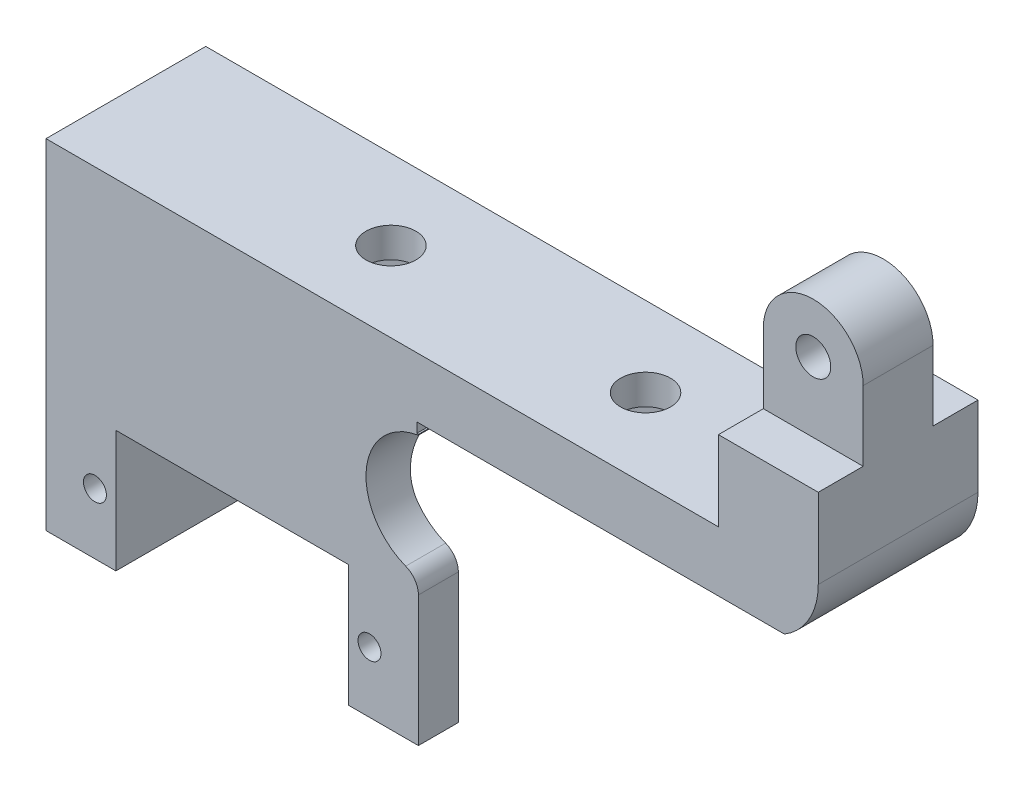
SolidWorks part; units mm, degrees
ref_plane "Plan de face" through (0, 0, 0) normal (0, 0, 1) x (1, 0, 0)
ref_plane "Plan de dessus" through (0, 0, 0) normal (0, 1, 0) x (1, 0, 0)
ref_plane "Plan de droite" through (0, 0, 0) normal (1, 0, 0) x (0, 0, -1)
sketch "Esquisse1" plane through (0, 0, 0) normal (0, 0, 1) x (1, 0, 0)
  line L0 (0, 0) -> (67.35, 0)
  line L1 (67.35, 0) -> (67.35, 20)
  line L2 (67.35, 20) -> (77.35, 20)
  line L3 (0, 0) -> (0, -34)
  line L4 (0, -34) -> (7, -34)
  line L5 (7, -34) -> (7, -7)
  line L6 (7, -7) -> (30.3, -7)
  line L7 (30.3, -7) -> (30.3, -34)
  line L8 (30.3, -34) -> (37.3, -34)
  line L9 (37.3, -34) -> (37.3, -7)
  line L10 (37.3, -7) -> (77.35, -7)
  line L11 (77.35, -7) -> (77.35, 20)
  line L12 (4.9, -27.9) -> (32.4, -27.9) construction
  line L13 (18.65, -27.9) -> (18.65, -7) construction
  circle A0 centre (4.9, -27.9) radius 1.15
  circle A1 centre (32.4, -27.9) radius 1.15
  dimension "D8" = 2.3
  dimension "D1" = 27
  dimension "D2" = 7
  dimension "D3" = 7
  dimension "D4" = 23.3
  dimension "D5" = 40.05
  dimension "D6" = 10
  dimension "D7" = 20
  dimension "D9" = 6.1
  dimension "D10" = 27.5
extrude "Boss.-Extru.1" add sketch "Esquisse1" along normal blind 16
sketch "Esquisse5" plane through (0, 20, 0) normal (0, 1, 0) x (1, 0, 0)
  line L0 (67.35, -16) -> (67.35, 0) construction
  line L1 (77.35, 0) -> (67.35, 0)
  line L2 (77.35, 0) -> (77.35, -4.5)
  line L3 (77.35, -4.5) -> (67.35, -4.5)
  line L4 (67.35, 0) -> (67.35, -4.5)
  line L6 (77.35, -16) -> (67.35, -16)
  line L7 (77.35, -16) -> (77.35, -11.5)
  line L8 (77.35, -11.5) -> (67.35, -11.5)
  line L9 (67.35, -16) -> (67.35, -11.5)
  dimension "D1" = 7
extrude "Enlèv. mat.-Extru.3" cut sketch "Esquisse5" against normal blind 12
sketch "Esquisse6" plane through (0, 0, 11.5) normal (0, 0, 1) x (1, 0, 0)
  line L0 (67.35, 15) -> (65.3495, 15)
  line L1 (65.3495, 15) -> (65.3495, 22.0005)
  line L2 (65.3495, 22.0005) -> (79.3505, 22.0005)
  line L4 (67.35, 8) -> (67.35, 20) construction
  line L5 (77.35, 8) -> (77.35, 20) construction
  line L6 (77.35, 20) -> (67.35, 20) construction
  line L7 (77.35, 15) -> (79.3505, 15)
  line L8 (79.3505, 15) -> (79.3505, 22.0005)
  line L9 (72.35, 20) -> (72.35, 22.0005) construction
  circle A0 centre (72.35, 15) radius 1.75
  circle A1 centre (72.35, 15) radius 5 construction
  arc A2 (67.35, 15) -> (77.35, 15) centre (72.35, 15) cw
  dimension "D1" = 3.5
  dimension "D2" = 2.0005
extrude "Enlèv. mat.-Extru.4" cut sketch "Esquisse6" against normal through all
sketch "Esquisse12" plane through (0, -34, 0) normal (0, -1, 0) x (-1, 0, 0)
  line L1 (-30.3, 0) -> (-37.3, 0)
  line L2 (-30.3, 0) -> (-30.3, -12)
  line L3 (-30.3, -12) -> (-37.3, -12)
  line L4 (-37.3, 0) -> (-37.3, -12)
  line L6 (-37.3, -16) -> (-37.3, 0) construction
  line L7 (-30.3, -16) -> (-37.3, -16) construction
  dimension "D1" = 4
extrude "Enlèv. mat.-Extru.7" cut sketch "Esquisse12" against normal up to surface (27 mm away) up to face at (18.65, -7, 8)
sketch "Esquisse14" plane through (0, 0, 16) normal (0, 0, 1) x (1, 0, 0)
  line L0 (30.3, -7) -> (30.3, -34) construction
  line L1 (7, -7) -> (30.3, -7)
  line L2 (7, -7) -> (7, -21.8)
  line L3 (7, -21.8) -> (30.3, -21.8)
  line L4 (30.3, -7) -> (30.3, -21.8)
  line L5 (32.4, -34) -> (32.4, -21.8) construction
  line L6 (30.3, -34) -> (37.3, -34) construction
  line L7 (32.4, -21.8) -> (30.3, -21.8) construction
  circle A0 centre (32.4, -27.9) radius 1.15 construction
  point P11 (32.4, -27.9)
extrude "Boss.-Extru.2" add sketch "Esquisse14" against normal up to surface (4 mm away) up to face at (33.55, -27.9, 12)
fillet "Congé1" radius 10 2 edges at (22.15, -7, 12) (7, -7, 6)
sketch "Esquisse15" plane through (0, 0, 16) normal (0, 0, 1) x (1, 0, 0)
  line L0 (37.3, -7) -> (77.35, -7) construction
  line L1 (37.3, -34) -> (37.3, -7) construction
  circle A0 centre (38.3, -13.25) radius 6.25
  dimension "D1" = 12.5
  dimension "D2" = 1
extrude "Enlèv. mat.-Extru.8" cut sketch "Esquisse15" against normal blind 18
fillet "Congé2" radius 2 1 edges at (37.3, -19.4195, 14)
fillet "Congé3" radius 7 1 edges at (77.35, -7, 8)
ref_plane "Plan1" through (0, 0, 8) normal (0, 0, -1) x (-1, 0, 0)
sketch "Esquisse16" plane through (0, 0, 8) normal (0, 0, -1) x (-1, 0, 0)
  line L0 (-52.05, 0) -> (-52.05, -7)
  line L1 (-52.05, -7) -> (-48.05, -7) construction
  line L2 (-48.05, -7) -> (-49.55, -5.5)
  line L3 (-49.55, -5.5) -> (-49.55, 0)
  line L4 (-49.55, 0) -> (-52.05, 0)
  line L5 (-37.3, -7) -> (-47.3, -7) construction
  line L6 (-24.55, 0) -> (-28.55, 0) construction
  line L8 (-48.05, -7) -> (-52.05, -7) construction
  line L9 (-48.05, -7) -> (-48.05, -57)
  line L10 (-48.05, -57) -> (-52.05, -57)
  line L11 (-52.05, -7) -> (-52.05, -57)
  dimension "D1" = 25.3
  dimension "D2" = 2.5
  dimension "D3" = 1.5
  dimension "D4" = 1.5
  dimension "D5" = 50
revolve "Enlèvement de matière-Révolution1" cut sketch "Esquisse16" angle 360 about L0
pattern_linear "Répétition linéaire1" count 2 spacing 25.5 along (-1, 0, 0) of "Enlèvement de matière-Révolution1"
sketch "Esquisse17" plane through (77.35, 0, 0) normal (1, 0, 0) x (0, 0, -1)
  line L0 (-9, -7) -> (-16, -6)
  line L1 (-16, -6) -> (-16, -7)
  line L2 (-16, -7) -> (-9, -7)
  dimension "D1" = 1
  dimension "D2" = 7
extrude "Enlèv. mat.-Extru.9" cut sketch "Esquisse17" against normal blind 40.2137
sketch "Esquisse18" plane through (0, -7, 0) normal (0, -1, 0) x (1, 0, 0)
  line L0 (56.2, 10.396) -> (56.2, 5.604)
  line L1 (56.2, 5.604) -> (52.05, 3.208)
  line L2 (52.05, 3.208) -> (47.9, 5.604)
  line L3 (47.9, 5.604) -> (47.9, 10.396)
  line L4 (47.9, 10.396) -> (52.05, 12.792)
  line L5 (52.05, 12.792) -> (56.2, 10.396)
  circle A0 centre (52.05, 8) radius 4.792 construction
  dimension "D1" = 8.3
extrude "Enlèv. mat.-Extru.10" cut sketch "Esquisse18" against normal blind 4 and the other way through all
pattern_linear "Répétition linéaire2" count 2 spacing 25.5 along (-1, 0, 0) of "Enlèv. mat.-Extru.10"
